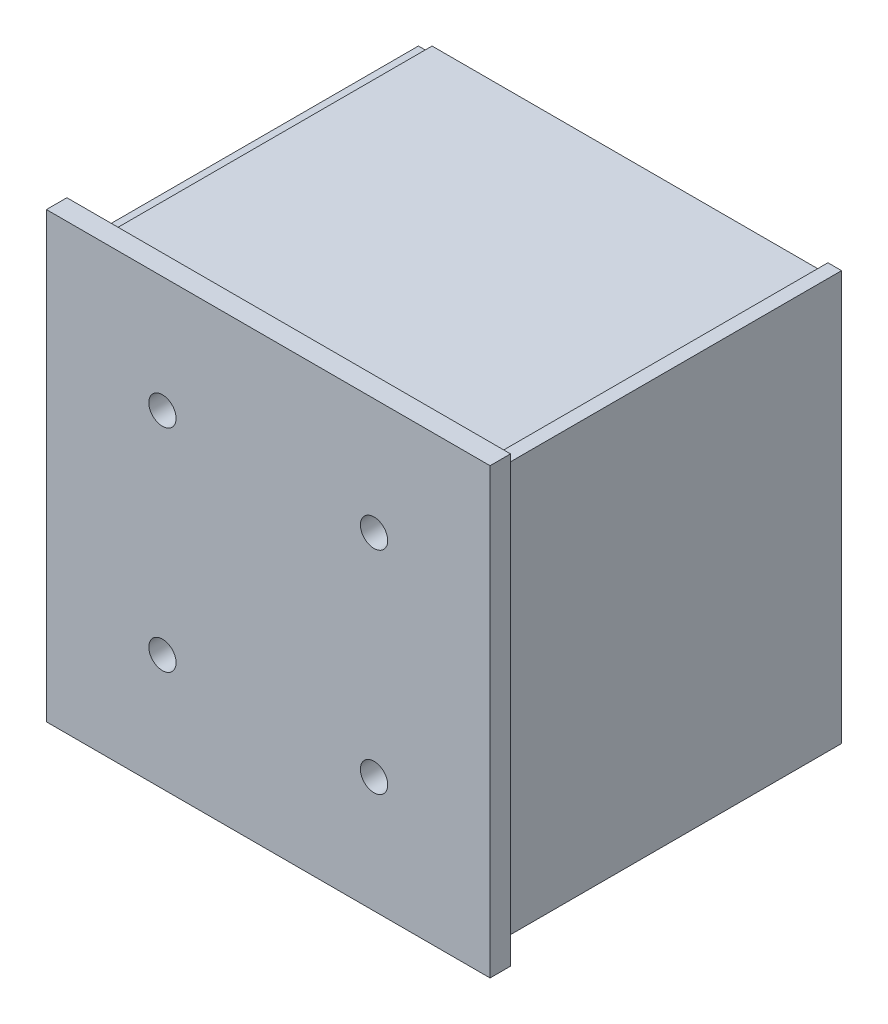
SolidWorks part; units mm, degrees
ref_plane "Front Plane" through (0, 0, 0) normal (0, 0, 1) x (1, 0, 0)
ref_plane "Top Plane" through (0, 0, 0) normal (0, 1, 0) x (1, 0, 0)
ref_plane "Right Plane" through (0, 0, 0) normal (1, 0, 0) x (0, 0, -1)
sketch "Sketch1" plane through (0, 0, 0) normal (0, 0, 1) x (1, 0, 0)
  line L0 (-15.5, 15.5) -> (-15.5, -15.5) construction
  line L1 (-32.5, 32.5) -> (32.5, 32.5)
  line L2 (-32.5, 32.5) -> (-32.5, -32.5)
  line L3 (-32.5, -32.5) -> (32.5, -32.5)
  line L4 (32.5, 32.5) -> (32.5, -32.5)
  line L5 (-32.5, 32.5) -> (32.5, -32.5) construction
  line L6 (-32.5, -32.5) -> (32.5, 32.5) construction
  line L7 (-15.5, -15.5) -> (15.5, -15.5) construction
  line L8 (15.5, -15.5) -> (15.5, 15.5) construction
  line L9 (15.5, 15.5) -> (-15.5, 15.5) construction
  circle A0 centre (-15.5, 15.5) radius 2
  circle A1 centre (15.5, 15.5) radius 2
  circle A2 centre (15.5, -15.5) radius 2
  circle A3 centre (-15.5, -15.5) radius 2
  point P0 (0, 0)
  point P14 (0, 0)
  dimension "D4" = 4
  dimension "D1" = 65
  dimension "D2" = 65
  dimension "D3" = 31
extrude "Boss-Extrude1" add sketch "Sketch1" along normal blind 3
sketch "Sketch4" plane through (0, 0, 0) normal (0, 0, -1) x (-1, 0, 0)
  line L0 (-30, 27.5) -> (30, 27.5) construction
  line L1 (30, 27.5) -> (30, -27.5) construction
  line L2 (30, -27.5) -> (-30, -27.5) construction
  line L3 (-30, -27.5) -> (-30, 27.5) construction
  line L4 (-32.5, 32.5) -> (-32.5, -32.5)
  line L5 (-32.5, -32.5) -> (32.5, -32.5)
  line L6 (32.5, -32.5) -> (32.5, 32.5)
  line L7 (32.5, 32.5) -> (-32.5, 32.5)
  line L8 (-32.5, 32.5) -> (-32.5, -32.5)
  line L9 (-32.5, -32.5) -> (32.5, -32.5)
  line L10 (32.5, -32.5) -> (32.5, 32.5)
  line L11 (32.5, 32.5) -> (-32.5, 32.5)
  line L12 (29, 28.5) -> (31, 28.5)
  line L13 (-29, -30) -> (-31, -30)
  line L14 (-29, -30) -> (-29, 30)
  line L15 (-29, 30) -> (-31, 30)
  line L16 (-31, -30) -> (-31, 30)
  line L17 (-29, -30) -> (-31, 30) construction
  line L18 (-29, 30) -> (-31, -30) construction
  line L19 (31, -27.5) -> (29, -27.5)
  line L20 (31, -27.5) -> (31, 27.5)
  line L21 (31, 27.5) -> (29, 27.5)
  line L22 (29, -27.5) -> (29, 27.5)
  line L23 (31, -27.5) -> (29, 27.5) construction
  line L24 (31, 27.5) -> (29, -27.5) construction
  line L25 (-29, 28.5) -> (29, 28.5)
  line L26 (-29, 28.5) -> (-29, 26.5)
  line L27 (-29, 26.5) -> (29, 26.5)
  line L28 (29, 28.5) -> (29, 26.5)
  line L29 (-29, 28.5) -> (29, 26.5) construction
  line L30 (-29, 26.5) -> (29, 28.5) construction
  line L31 (-29, -26.5) -> (29, -26.5)
  line L32 (-29, -26.5) -> (-29, -28.5)
  line L33 (-29, -28.5) -> (29, -28.5)
  line L34 (29, -26.5) -> (29, -28.5)
  line L35 (-29, -26.5) -> (29, -28.5) construction
  line L36 (-29, -28.5) -> (29, -26.5) construction
  line L37 (31, 28.5) -> (31, 27.5)
  point P2 (0, -27.5)
  point P6 (30, 0)
  point P10 (-30, 0)
  point P16 (30, 0)
  point P21 (0, 27.5)
  point P26 (0, -27.5)
  dimension "D2" = 60
  dimension "D3" = 55
  dimension "D4" = 60
  dimension "D5" = 2
  dimension "D6" = 2
  dimension "D7" = 2
  dimension "D8" = 2
  dimension "D1" = 0
extrude "Boss-Extrude3" add sketch "Sketch4" along normal blind 50 contours L16 L13 L14 L15 | L34 L22 L31 L14 L32 L33 | L22 L19 L20 L21 | L28 L25 L26 L14 L27 L22
